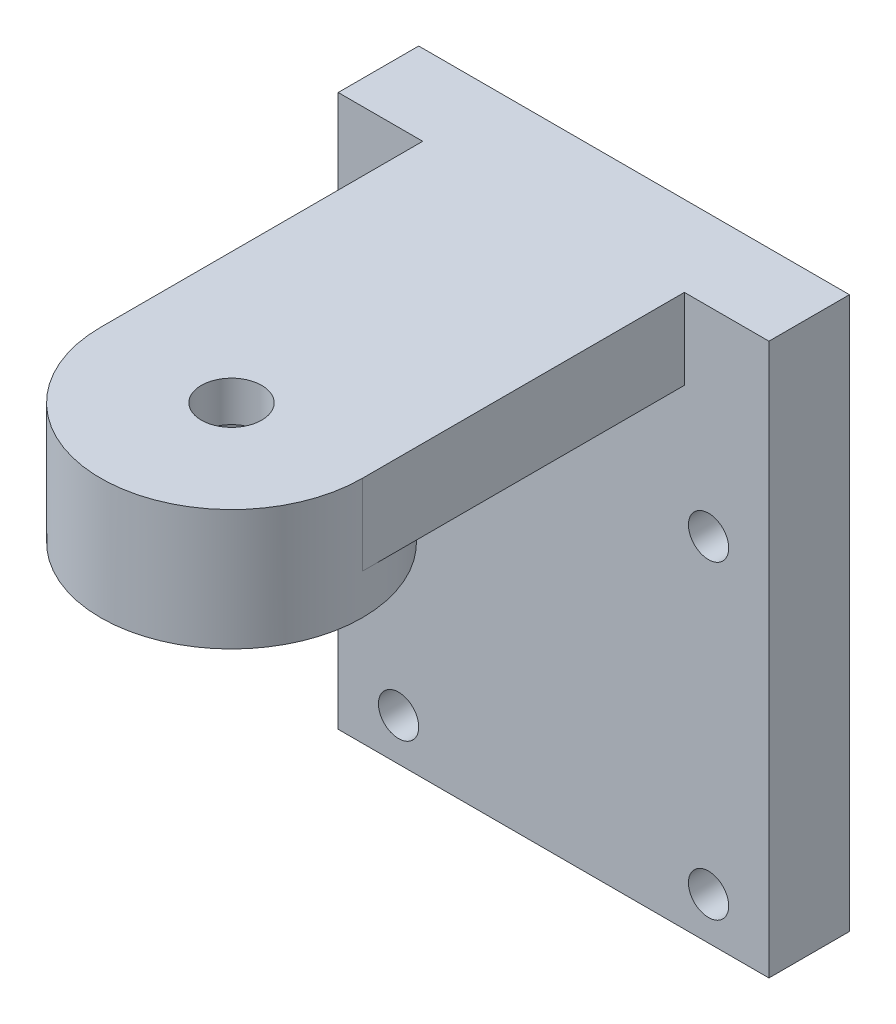
SolidWorks part; units mm, degrees
material "3.0205 (EN-AW 1200)"
ref_plane "前视基准面" through (0, 0, 0) normal (0, 0, 1) x (1, 0, 0)
ref_plane "上视基准面" through (0, 0, 0) normal (0, 1, 0) x (1, 0, 0)
ref_plane "右视基准面" through (0, 0, 0) normal (1, 0, 0) x (0, 0, -1)
sketch "草图1" plane through (0, 0, 0) normal (0, 1, 0) x (1, 0, 0)
  line L1 (5, 0) -> (2.5, 4.3301)
  line L2 (2.5, 4.3301) -> (-2.5, 4.3301)
  line L3 (-2.5, 4.3301) -> (-5, 0)
  line L4 (-5, 0) -> (-2.5, -4.3301)
  line L5 (-2.5, -4.3301) -> (2.5, -4.3301)
  line L6 (5, 0) -> (2.5, -4.3301)
sketch "草图2" plane through (0, 0, 0) normal (0, 1, 0) x (1, 0, 0)
  circle A0 centre (0, 0) radius 6.5
extrude "凸台-拉伸1" add sketch "草图2" along normal blind 6
extrude "切除-拉伸1" cut sketch "草图1" along normal blind 4
sketch "草图3" plane through (0, 6, 0) normal (0, 1, 0) x (1, 0, 0)
  circle A0 centre (0, 0) radius 1.5
extrude "切除-拉伸2" cut sketch "草图3" against normal blind 4
sketch "草图4" plane through (0, 6, 0) normal (0, 1, 0) x (1, 0, 0)
  line L1 (6.5, 20) -> (4, 20)
  line L3 (-6.5, 0) -> (-6.5, 20)
  line L4 (-6.5, 20) -> (-4, 20)
  line L7 (-6.5, 0) -> (6.5, 0)
  line L8 (6.5, 0) -> (6.5, 20)
  line L11 (-4, 20) -> (4, 20)
  circle A0 centre (0, 0) radius 6.5 construction
  circle A1 centre (0, 0) radius 6.5
extrude "凸台-拉伸2" add sketch "草图4" against normal blind 4
sketch "草图6" plane through (0, 0, -20) normal (0, 0, -1) x (-1, 0, 0)
  line L0 (10.7, 6) -> (-10.7, 6)
  line L1 (10.7, 6) -> (10.7, -21.4)
  line L2 (-10.7, 6) -> (10.7, 6)
  line L7 (10.7, 6) -> (10.7, -14.2408)
  line L8 (10.7, -21.4) -> (-10.7, -21.4)
  line L9 (-10.7, -21.4) -> (-10.7, 6)
extrude "凸台-拉伸6" add sketch "草图6" against normal blind 4
sketch "草图17" plane through (0, 0, -16) normal (0, 0, 1) x (1, 0, 0)
  circle A0 centre (-7.7, -19.3) radius 1
  circle A1 centre (7.7, -19.3) radius 1
  circle A2 centre (7.7, -3.9) radius 1
  circle A3 centre (-7.7, -3.9) radius 1
extrude "切除-拉伸11" cut sketch "草图17" against normal blind 4
